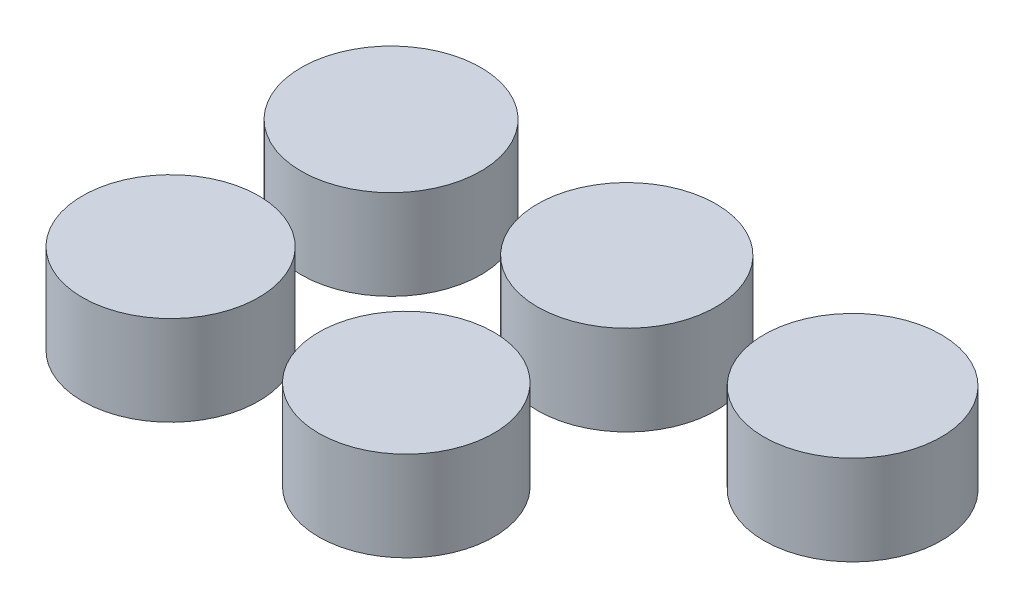
SolidWorks part; units mm, degrees
ref_plane "Front Plane" through (0, 0, 0) normal (0, 0, 1) x (1, 0, 0)
ref_plane "Top Plane" through (0, 0, 0) normal (0, 1, 0) x (1, 0, 0)
ref_plane "Right Plane" through (0, 0, 0) normal (1, 0, 0) x (0, 0, -1)
sketch "Sketch1" plane through (0, 0, 0) normal (0, 1, 0) x (1, 0, 0)
  circle A0 centre (0, 0) radius 4
  circle A1 centre (10.4966, 0) radius 3.975
  circle A2 centre (20.5558, 0) radius 3.95
  circle A3 centre (0, -9.8189) radius 3.925
  circle A4 centre (10.4966, -9.8189) radius 3.9
  point P11 (0, -9.8189)
  point P12 (10.4966, 0)
  point P13 (10.4966, -9.8189)
  point P14 (20.5558, 0)
  dimension "D1" = 8
  dimension "D2" = 7.95
  dimension "D3" = 7.9
  dimension "D4" = 7.85
  dimension "D5" = 7.8
extrude "Boss-Extrude1" add sketch "Sketch1" along normal blind 4
